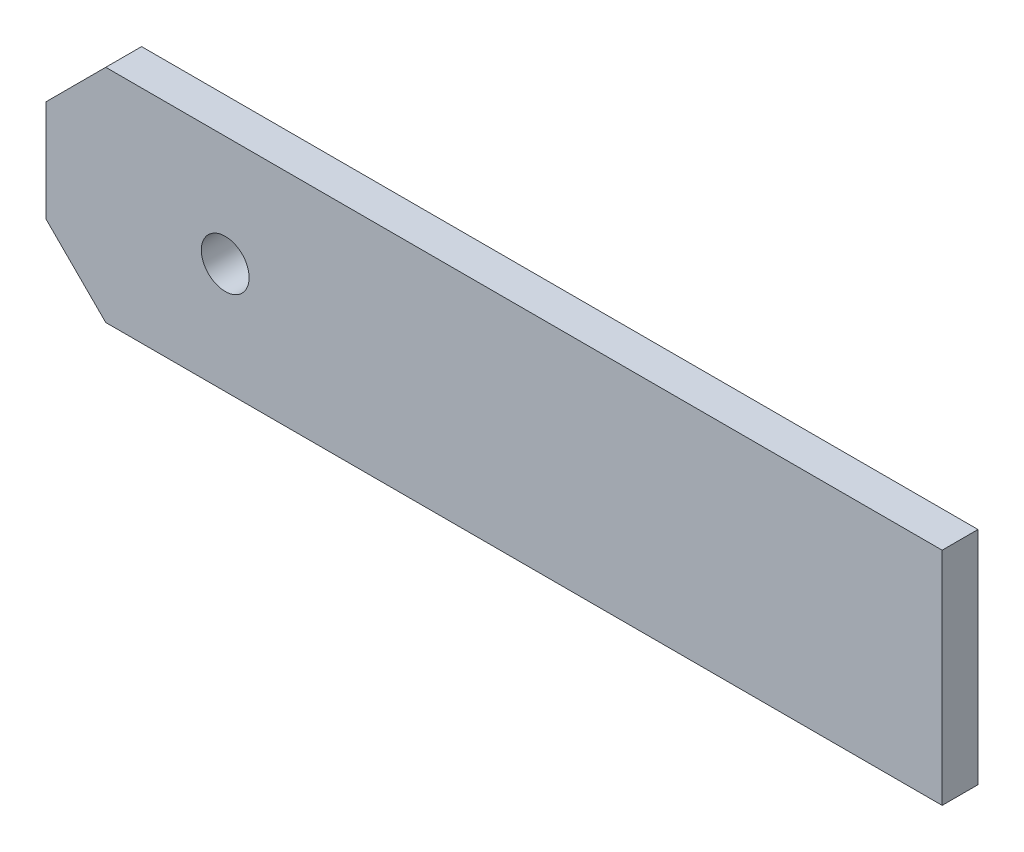
SolidWorks part; units mm, degrees
material "Acrylic (Medium-high impact)"
ref_plane "Front Plane" through (0, 0, 0) normal (0, 0, 1) x (1, 0, 0)
ref_plane "Top Plane" through (0, 0, 0) normal (0, 1, 0) x (1, 0, 0)
ref_plane "Right Plane" through (0, 0, 0) normal (1, 0, 0) x (0, 0, -1)
sketch "Sketch1" plane through (0, 0, 0) normal (0, 0, 1) x (1, 0, 0)
  line L1 (-997.4157, 66.1348) -> (-857.4157, 66.1348)
  line L2 (-1007.4157, 56.1348) -> (-1007.4157, 39.1348)
  line L3 (-997.4157, 29.1348) -> (-857.4157, 29.1348)
  line L6 (-1007.4157, 56.1348) -> (-997.4157, 66.1348)
  line L7 (-857.4157, 66.1348) -> (-857.4157, 29.1348)
  line L8 (-1007.4157, 39.1348) -> (-997.4157, 29.1348)
  circle A0 centre (-977.4157, 47.6348) radius 4
  point P0 (-1007.4157, 66.1348)
  point P2 (-1007.4157, 29.1348)
  point P10 (-1007.4157, 45.5904)
  dimension "D3" = 8
  dimension "D1" = 37
  dimension "D2" = 150
  dimension "D4" = 18.5
  dimension "D5" = 30
extrude "Boss-Extrude1" add sketch "Sketch1" along normal blind 6
